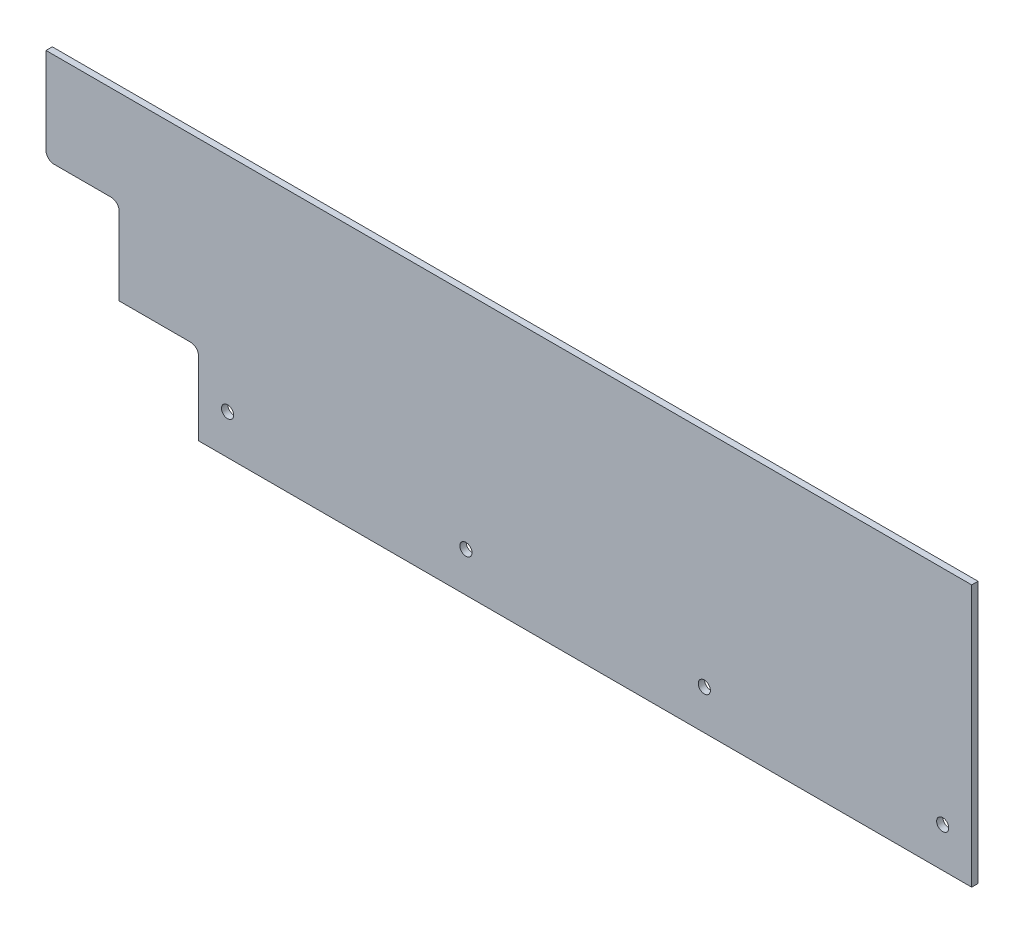
SolidWorks part; units mm, degrees
ref_plane "Front Plane" through (0, 0, 0) normal (0, 0, 1) x (1, 0, 0)
ref_plane "Top Plane" through (0, 0, 0) normal (0, 1, 0) x (1, 0, 0)
ref_plane "Right Plane" through (0, 0, 0) normal (1, 0, 0) x (0, 0, -1)
sketch "Sketch1" plane through (0, 0, 0) normal (0, 0, 1) x (1, 0, 0)
  line L0 (-466, 131.8) -> (0, 131.8)
  line L1 (0, 20) -> (-389.2, 20) construction
  line L2 (-194.6, 0) -> (-194.6, 131.8) construction
  line L4 (0, 0) -> (0, 131.8)
  line L12 (0, 0) -> (-389.2, 0)
  line L13 (-429.2, 80.2) -> (-429.2, 41)
  line L14 (-429.2, 41) -> (-393.2, 41)
  line L15 (-389.2, 37) -> (-389.2, 0)
  line L16 (-433.2, 84.2) -> (-462, 84.2)
  line L18 (-466, 88.2) -> (-466, 131.8)
  arc A0 (-429.2, 80.2) -> (-433.2, 84.2) centre (-433.2, 80.2) ccw
  circle A1 centre (-14.6, 20) radius 0.1563
  circle A2 centre (-14.6, 20) radius 3.05
  circle A3 centre (-134.6, 20) radius 3.05
  circle A4 centre (-254.6, 20) radius 3.05
  circle A5 centre (-374.6, 20) radius 3.05
  arc A10 (-389.2, 37) -> (-393.2, 41) centre (-393.2, 37) ccw
  arc A12 (-466, 88.2) -> (-462, 84.2) centre (-462, 88.2) ccw
  dimension "D2" = 6.1
  dimension "D3" = 4
  dimension "D4" = 120
  dimension "D11" = 4
  dimension "D1" = 20
  dimension "D5" = 466
  dimension "D6" = 40
  dimension "D7" = 36.8
  dimension "D8" = 131.8
  dimension "D9" = 41
  dimension "D10" = 43.2
extrude "Boss-Extrude1" add sketch "Sketch1" along normal blind 3.175 contours L18 A12 L16 A0 L13 L14 A10 L15 L12 L4 L0 A2 A3 A4 A5
